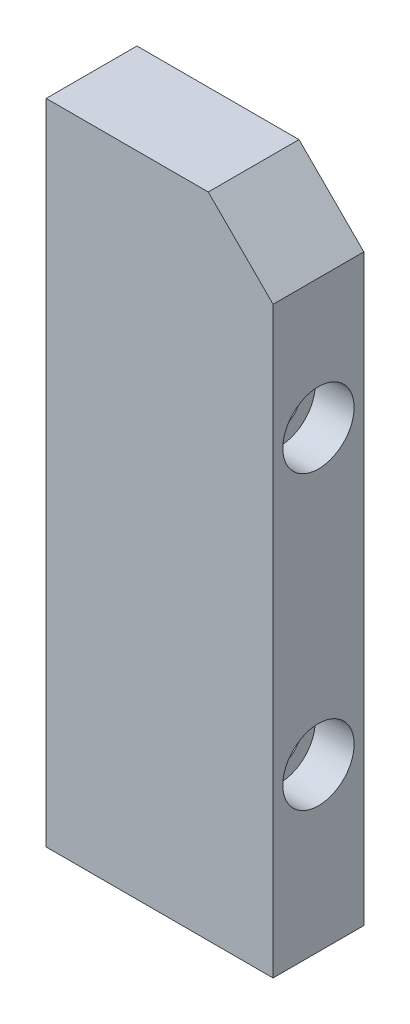
SolidWorks part; units mm, degrees
material "1.0037 (S235JR)"
ref_plane "Płaszczyzna przednia" through (0, 0, 0) normal (0, 0, 1) x (1, 0, 0)
ref_plane "Płaszczyzna górna" through (0, 0, 0) normal (0, 1, 0) x (1, 0, 0)
ref_plane "Płaszczyzna prawa" through (0, 0, 0) normal (1, 0, 0) x (0, 0, -1)
sketch "Szkic1" plane through (0, 0, 0) normal (0, 0, 1) x (1, 0, 0)
  line L1 (0, 0) -> (35, 0)
  line L2 (0, 0) -> (0, 100)
  line L3 (0, 100) -> (35, 100)
  line L4 (35, 0) -> (35, 100)
  dimension "D1" = 35
  dimension "D2" = 100
extrude "Dodanie-wyciągnięcie1" add sketch "Szkic1" along normal blind 14
chamfer "Sfazowanie1" distance 10 angle 45 1 edges at (35, 100, 7)
hole_wizard "Pogłębienie walcowe pod M6 Wkręt do części metalowych z łbem sześciokątnym1" positions "Szkic3" profile "Szkic2" counterbore size "M6" standard "Ansi Metric" end condition through all
sketch "Szkic3" plane through (35, 0, 0) normal (1, 0, 0) x (0, 0, -1)
  line L0 (-7, 0) -> (-7, 90) construction
  line L1 (-14, 0) -> (0, 0) construction
  line L2 (0, 90) -> (-14, 90) construction
  point P0 (-7, 70)
  point P2 (-7, 25)
  dimension "D1" = 25
  dimension "D2" = 45
sketch "Szkic2" plane through (35, 70, 7) normal (0, 1, 0) x (0, 0, -1)
  line L0 (0, 0) -> (0, 35)
  line L1 (0, 35) -> (3.25, 35)
  line L3 (3.25, 35) -> (3.25, 6)
  line L4 (3.25, 6) -> (5.5, 6)
  line L5 (5.5, 6) -> (5.5, 0)
  line L7 (5.5, 0) -> (0, 0)
  line L11 (0, -6.35) -> (0, 107.95) construction
  dimension "Średnica otworu na wylot" = 6.5
  dimension "Głębokość otworu na wylot" = 35
  dimension "Średnica pogłębienia walcowego" = 11
  dimension "Głębokość pogłębienia walcowego" = 6
hole_wizard "Otwór gwintowany M6x1.01" positions "Szkic5" profile "Szkic4" tap size "M6x1.0" standard "Ansi Metric"
sketch "Szkic5" plane through (0, 0, 0) normal (0, -1, 0) x (-1, 0, 0)
  point P0 (-17.5, -7)
sketch "Szkic4" plane through (17.5, 0, 7) normal (1, 0, 0) x (0, 0, -1)
  line L0 (0, 0) -> (0, 18.5022)
  line L1 (0, 18.5022) -> (2.5, 17)
  line L2 (2.5, 17) -> (2.5, 0)
  line L5 (2.5, 0) -> (0, 0)
  line L10 (0, 18.5022) -> (-2.5, 17) construction
  line L11 (0, -6.35) -> (0, 107.95) construction
  dimension "Średnica wiertła gwintu" = 5
  dimension "Głębokość otworu gwintowanego" = 17
  dimension "Kąt wiertła" = 118
cosmetic thread "Gwint otworu1" parameters "D1"=12, "D2"=6
